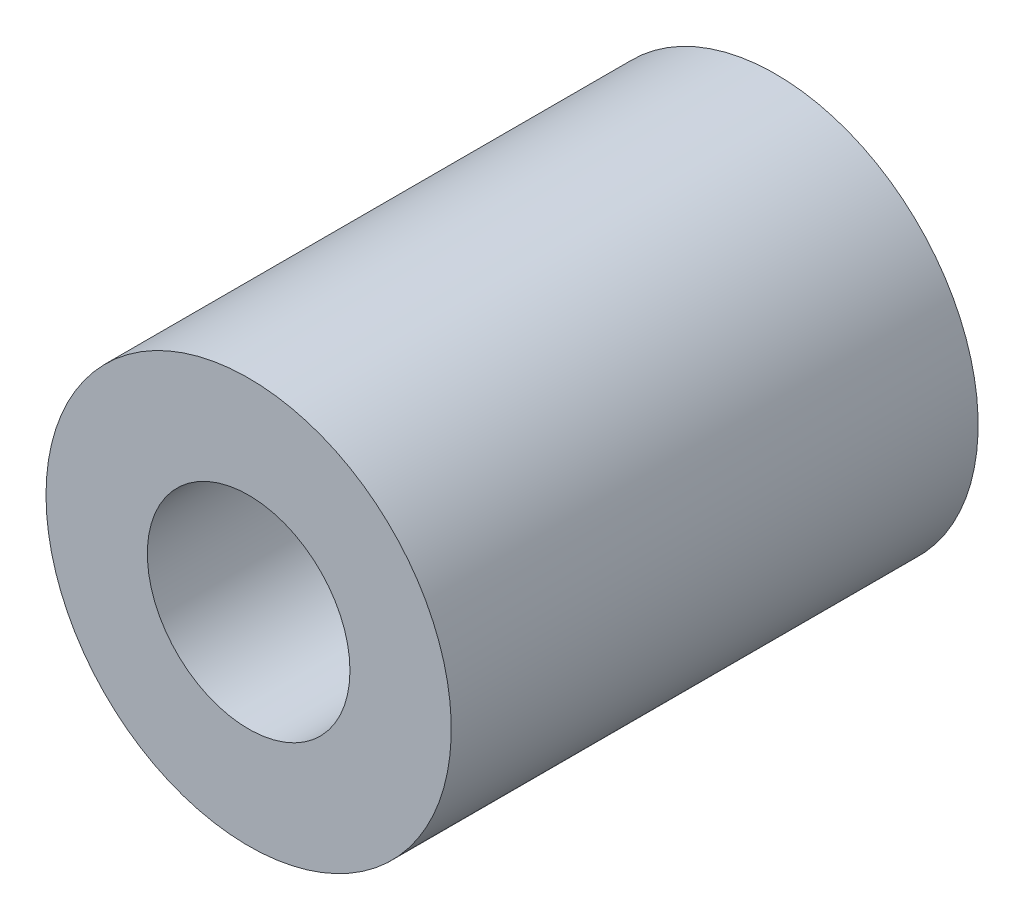
SolidWorks part; units mm, degrees
ref_plane "Front Plane" through (0, 0, 0) normal (0, 0, 1) x (1, 0, 0)
ref_plane "Top Plane" through (0, 0, 0) normal (0, 1, 0) x (1, 0, 0)
ref_plane "Right Plane" through (0, 0, 0) normal (1, 0, 0) x (0, 0, -1)
sketch "Sketch1" plane through (0, 0, 0) normal (0, 0, 1) x (1, 0, 0)
  circle A0 centre (0, 0) radius 10
  dimension "D1" = 20
extrude "Boss-Extrude1" add sketch "Sketch1" along normal blind 26
sketch "Sketch2" plane through (0, 0, 26) normal (0, 0, 1) x (1, 0, 0)
  circle A0 centre (0, 0) radius 5
  dimension "D1" = 10
extrude "Cut-Extrude1" cut sketch "Sketch2" against normal blind 8
sketch "Sketch3" plane through (0, 0, 0) normal (0, 0, -1) x (-1, 0, 0)
  circle A0 centre (0, 0) radius 2
  dimension "D1" = 4
extrude "Cut-Extrude2" cut sketch "Sketch3" against normal blind 8
